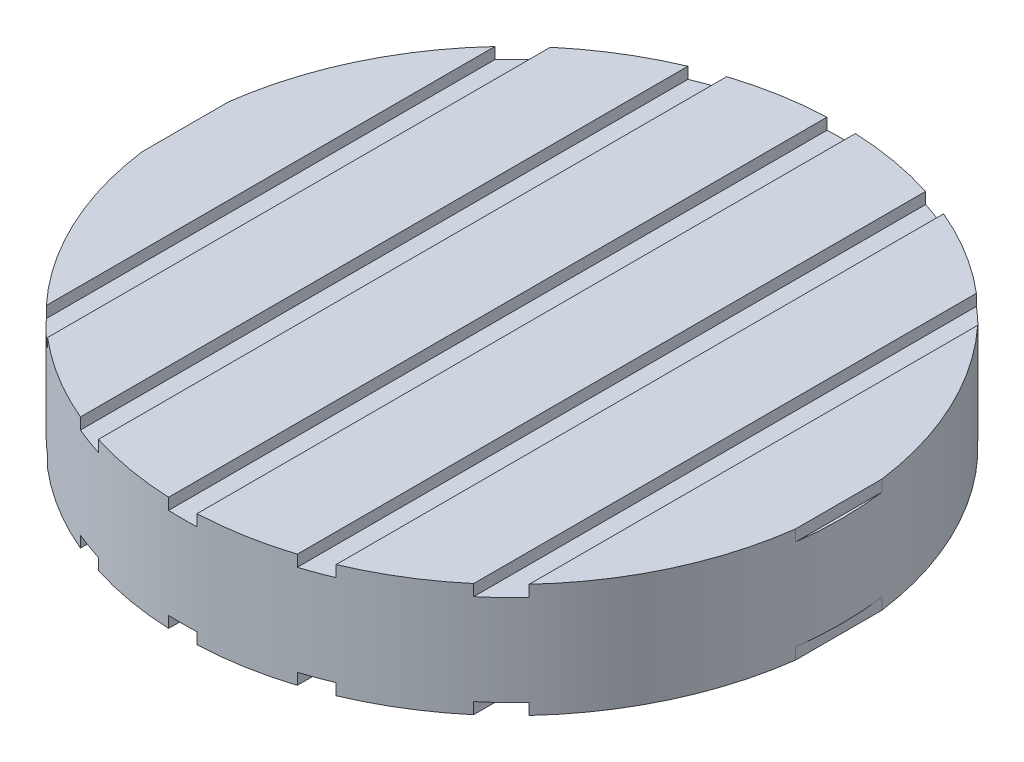
SolidWorks part; units mm, degrees
ref_plane "Front Plane" through (0, 0, 0) normal (0, 0, 1) x (1, 0, 0)
ref_plane "Top Plane" through (0, 0, 0) normal (0, 1, 0) x (1, 0, 0)
ref_plane "Right Plane" through (0, 0, 0) normal (1, 0, 0) x (0, 0, -1)
sketch "Sketch1" plane through (0, 0, 0) normal (0, 1, 0) x (1, 0, 0)
  circle A0 centre (-5.3482, -2.1046) radius 2.9
  dimension "D1" = 5.8
extrude "Boss-Extrude1" add sketch "Sketch1" along normal blind 1
sketch "Sketch2" plane through (0, 1, 0) normal (0, 1, 0) x (1, 0, 0)
  line L0 (-10.4732, 0.7954) -> (-10.4732, -5.0046)
  line L1 (-11.4732, 0.7954) -> (-11.2232, 0.7954)
  line L2 (-11.4732, 0.7954) -> (-11.4732, -5.0046)
  line L3 (-11.4732, -5.0046) -> (-11.2232, -5.0046)
  line L4 (-11.2232, 0.7954) -> (-11.2232, -5.0046)
  line L5 (-10.4732, 0.7954) -> (-10.2232, 0.7954)
  line L6 (-10.2232, 0.7954) -> (-10.2232, -5.0046)
  line L7 (-10.4732, -5.0046) -> (-10.2232, -5.0046)
  line L8 (-9.4732, 0.7954) -> (-9.4732, -5.0046)
  line L9 (-9.4732, 0.7954) -> (-9.2232, 0.7954)
  line L10 (-9.2232, 0.7954) -> (-9.2232, -5.0046)
  line L11 (-9.4732, -5.0046) -> (-9.2232, -5.0046)
  line L12 (-8.4732, 0.7954) -> (-8.4732, -5.0046)
  line L13 (-8.4732, 0.7954) -> (-8.2232, 0.7954)
  line L14 (-8.2232, 0.7954) -> (-8.2232, -5.0046)
  line L15 (-8.4732, -5.0046) -> (-8.2232, -5.0046)
  line L16 (-7.4732, 0.7954) -> (-7.4732, -5.0046)
  line L17 (-7.4732, 0.7954) -> (-7.2232, 0.7954)
  line L18 (-7.2232, 0.7954) -> (-7.2232, -5.0046)
  line L19 (-7.4732, -5.0046) -> (-7.2232, -5.0046)
  line L20 (-6.4732, 0.7954) -> (-6.4732, -5.0046)
  line L21 (-6.4732, 0.7954) -> (-6.2232, 0.7954)
  line L22 (-6.2232, 0.7954) -> (-6.2232, -5.0046)
  line L23 (-6.4732, -5.0046) -> (-6.2232, -5.0046)
  line L24 (-5.4732, 0.7954) -> (-5.4732, -5.0046)
  line L25 (-5.4732, 0.7954) -> (-5.2232, 0.7954)
  line L26 (-5.2232, 0.7954) -> (-5.2232, -5.0046)
  line L27 (-5.4732, -5.0046) -> (-5.2232, -5.0046)
  line L28 (-4.4732, 0.7954) -> (-4.4732, -5.0046)
  line L29 (-4.4732, 0.7954) -> (-4.2232, 0.7954)
  line L30 (-4.2232, 0.7954) -> (-4.2232, -5.0046)
  line L31 (-4.4732, -5.0046) -> (-4.2232, -5.0046)
  line L32 (-3.4732, 0.7954) -> (-3.4732, -5.0046)
  line L33 (-3.4732, 0.7954) -> (-3.2232, 0.7954)
  line L34 (-3.2232, 0.7954) -> (-3.2232, -5.0046)
  line L35 (-3.4732, -5.0046) -> (-3.2232, -5.0046)
  line L36 (-2.4732, 0.7954) -> (-2.4732, -5.0046)
  line L37 (-2.4732, 0.7954) -> (-2.2232, 0.7954)
  line L38 (-2.2232, 0.7954) -> (-2.2232, -5.0046)
  line L39 (-2.4732, -5.0046) -> (-2.2232, -5.0046)
  line L40 (-1.4732, 0.7954) -> (-1.4732, -5.0046)
  line L41 (-1.4732, 0.7954) -> (-1.2232, 0.7954)
  line L42 (-1.2232, 0.7954) -> (-1.2232, -5.0046)
  line L43 (-1.4732, -5.0046) -> (-1.2232, -5.0046)
  line L44 (-0.4732, 0.7954) -> (-0.4732, -5.0046)
  line L45 (-0.4732, 0.7954) -> (-0.2232, 0.7954)
  line L46 (-0.2232, 0.7954) -> (-0.2232, -5.0046)
  line L47 (-0.4732, -5.0046) -> (-0.2232, -5.0046)
  line L48 (0.5268, 0.7954) -> (0.5268, -5.0046)
  line L49 (0.5268, 0.7954) -> (0.7768, 0.7954)
  line L50 (0.7768, 0.7954) -> (0.7768, -5.0046)
  line L51 (0.5268, -5.0046) -> (0.7768, -5.0046)
  line L52 (1.5268, 0.7954) -> (1.5268, -5.0046)
  line L53 (1.5268, 0.7954) -> (1.7768, 0.7954)
  line L54 (1.7768, 0.7954) -> (1.7768, -5.0046)
  line L55 (1.5268, -5.0046) -> (1.7768, -5.0046)
  line L56 (2.5268, 0.7954) -> (2.5268, -5.0046)
  line L57 (2.5268, 0.7954) -> (2.7768, 0.7954)
  line L58 (2.7768, 0.7954) -> (2.7768, -5.0046)
  line L59 (2.5268, -5.0046) -> (2.7768, -5.0046)
  line L60 (-11.4732, 0.7954) -> (-10.4732, 0.7954) construction
  circle A0 centre (-5.3482, -2.1046) radius 2.9 construction
  point P6 (-5.3482, 0.7954)
  dimension "D1" = 0.25
  dimension "D3" = 1
  dimension "D2" = 15
extrude "Cut-Extrude1" cut sketch "Sketch2" against normal blind 0.1
ref_plane "Plane1" through (0, 0.5, 0) normal (0, -1, 0) x (-1, 0, 0)
mirror "Mirror1" about plane through (0, 0.5, 0) normal (0, -1, 0) of "Cut-Extrude1"
